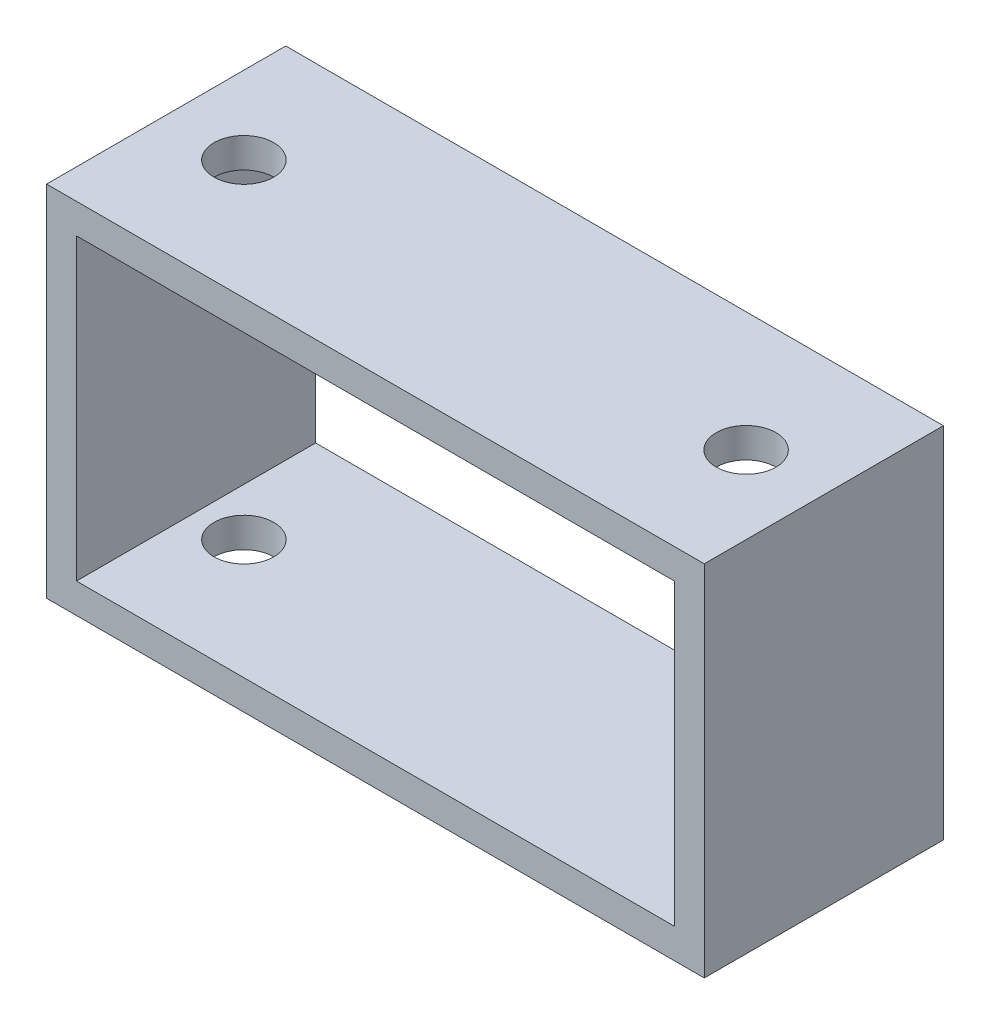
SolidWorks part; units mm, degrees
ref_plane "前视基准面" through (0, 0, 0) normal (0, 0, 1) x (1, 0, 0)
ref_plane "上视基准面" through (0, 0, 0) normal (0, 1, 0) x (1, 0, 0)
ref_plane "右视基准面" through (0, 0, 0) normal (1, 0, 0) x (0, 0, -1)
sketch "草图1" plane through (0, 0, 0) normal (0, 1, 0) x (1, 0, 0)
  line L0 (-27.5, 0) -> (27.5, 0) construction
  line L1 (-27.5, -10) -> (27.5, -10)
  line L2 (-27.5, -10) -> (-27.5, 10)
  line L3 (-27.5, 10) -> (27.5, 10)
  line L4 (27.5, -10) -> (27.5, 10)
  line L5 (-27.5, -10) -> (27.5, 10) construction
  line L6 (-27.5, 10) -> (27.5, -10) construction
  point P0 (0, 0)
  dimension "D1" = 20
  dimension "D2" = 55
extrude "凸台-拉伸1" add sketch "草图1" along normal blind 30
sketch "草图2" plane through (0, 0, 10) normal (0, 0, 1) x (1, 0, 0)
  line L0 (-27.5, 15) -> (27.5, 15) construction
  line L1 (-25, 2.5) -> (25, 2.5)
  line L2 (-25, 2.5) -> (-25, 27.5)
  line L3 (-25, 27.5) -> (25, 27.5)
  line L4 (25, 2.5) -> (25, 27.5)
  line L5 (-25, 2.5) -> (25, 27.5) construction
  line L6 (-25, 27.5) -> (25, 2.5) construction
  line L7 (-27.5, 30) -> (-27.5, 0) construction
  line L8 (27.5, 30) -> (27.5, 0) construction
  line L9 (0, 30) -> (0, 0) construction
  line L10 (-27.5, 30) -> (27.5, 30) construction
  point P0 (0, 15)
  point P16 (0, 15)
  dimension "D1" = 50
  dimension "D2" = 25
extrude "切除-拉伸1" cut sketch "草图2" against normal up to next
sketch "草图3" plane through (0, 30, 0) normal (0, 1, 0) x (1, 0, 0)
  line L0 (-27.5, 0) -> (27.5, 0) construction
  line L1 (-27.5, 10) -> (-27.5, -10) construction
  line L2 (27.5, -10) -> (27.5, 10) construction
  circle A0 centre (-21, 0) radius 2.5
  circle A1 centre (21, 0) radius 2.5
  dimension "D3" = 5
  dimension "D4" = 5
  dimension "D1" = 6.5
  dimension "D2" = 6.5
extrude "切除-拉伸2" cut sketch "草图3" against normal up to surface (30 mm away) up to face at (0, 0, 0)
